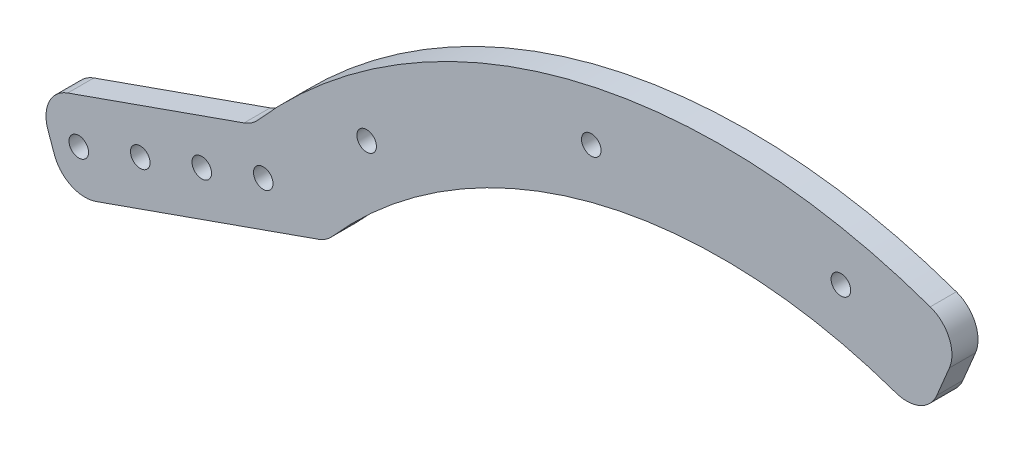
SolidWorks part; units mm, degrees
ref_plane "Front Plane" through (0, 0, 0) normal (0, 0, 1) x (1, 0, 0)
ref_plane "Top Plane" through (0, 0, 0) normal (0, 1, 0) x (1, 0, 0)
ref_plane "Right Plane" through (0, 0, 0) normal (1, 0, 0) x (0, 0, -1)
sketch "Sketch1" plane through (0, 0, 0) normal (0, 0, 1) x (1, 0, 0)
  line L0 (-132.022, 65.7897) -> (-212.1762, 37.5)
  line L1 (51.7662, 161.9592) -> (27.2426, 103.4517) construction
  line L2 (-154.8138, 85.297) -> (-220.8231, 61.9996) construction
  line L3 (-10.6861, 66.0459) -> (-10.9148, 174.3641) construction
  line L4 (-216.4997, 49.7498) -> (-207.0698, 53.078) construction
  line L5 (32.4547, 115.8865) -> (40.5023, 144.7869) construction
  line L6 (-154.8138, 85.297) -> (-220.8231, 61.9996)
  line L7 (-220.8231, 61.9996) -> (-212.1762, 37.5)
  line L8 (-47.4083, 117.4275) -> (-132.022, 65.7897) construction
  line L9 (-89.7151, 91.6086) -> (-121.1048, 143.0437) construction
  line L10 (122.3134, 57.5344) -> (77.0665, 91.5473) construction
  line L11 (-212.1762, 37.5) -> (-212.1762, 7.5) construction
  line L12 (-212.1762, 7.5) -> (-297.1762, 7.5) construction
  line L13 (-297.1762, 7.5) -> (-212.1762, 37.5) construction
  line L14 (-147.9866, 38.946) -> (-93.3561, 58.2274) construction
  line L15 (-93.3561, 58.2274) -> (51.385, 109.3125) construction
  line L16 (184.397, 188.9678) -> (-168.455, 103.7035) construction
  line L17 (51.385, 109.3125) -> (62.982, 136.9803) construction
  line L18 (-0.3193, 248.4877) -> (121.5642, -96.8487) construction
  line L19 (51.385, 109.3125) -> (62.982, 136.9803)
  line L20 (-132.022, 65.7897) -> (51.385, 109.3125) construction
  arc A1 (62.982, 136.9803) -> (-154.8138, 85.297) centre (-10.4659, -38.2493) ccw
  arc A2 (51.385, 109.3125) -> (-132.022, 65.7897) centre (-10.4659, -38.2493) ccw
  dimension "D1" = 30
  dimension "D4" = 160
  dimension "D5" = 190
  dimension "D2" = 85
  dimension "D3" = 25.9808
  dimension "D6" = 85
  dimension "D7" = 20
  dimension "D8" = 20
  dimension "D9" = 10
  dimension "D10" = 260
extrude "Boss-Extrude1" add sketch "Sketch1" along normal blind 8
sketch "Sketch2" plane through (0, 0, 8) normal (0, 0, 1) x (1, 0, 0)
  line L0 (-216.4997, 49.7498) -> (-123.9236, 82.4237) construction
  line L1 (-220.8231, 61.9996) -> (-212.1762, 37.5) construction
  line L3 (42.7389, 166.2908) -> (9.592, 87.2101) construction
  line L4 (51.385, 109.3125) -> (62.982, 136.9803) construction
  line L5 (-154.8138, 85.297) -> (-220.8231, 61.9996) construction
  line L6 (-132.022, 65.7897) -> (51.385, 109.3125) construction
  line L7 (-40.3185, 87.5511) -> (-44.5586, 105.4188) construction
  line L8 (-47.4083, 117.4275) -> (-54.2495, 146.2568) construction
  line L10 (22.6202, 118.2925) -> (115.0547, 98.7558) construction
  line L11 (22.6202, 118.2925) -> (28.8239, 147.644) construction
  circle A0 centre (-208.0128, 52.7452) radius 3
  circle A1 centre (-189.153, 59.4016) radius 3
  arc A2 (62.982, 136.9803) -> (-154.8138, 85.297) centre (-10.4659, -38.2493) ccw construction
  circle A3 centre (-170.2932, 66.058) radius 3
  circle A4 centre (-151.4334, 72.7144) radius 3
  circle A6 centre (25.722, 132.9682) radius 3
  arc A8 (51.385, 109.3125) -> (-132.022, 65.7897) centre (-10.4659, -38.2493) ccw construction
  circle A9 centre (-50.8289, 131.8422) radius 3
  arc A11 (51.385, 109.3125) -> (-132.022, 65.7897) centre (-10.4659, -38.2493) ccw construction
  circle A12 centre (-119.7239, 98.4537) radius 3
  dimension "D1" = 6
  dimension "D3" = 20
  dimension "D2" = 9
  dimension "D4" = 20
  dimension "D5" = 30
  dimension "D7" = 20
extrude "Cut-Extrude1" cut sketch "Sketch2" against normal offset from surface (7.8 mm away) 0.2 up to face at (-103.4962, 93.7056, 0)
fillet "Fillet1" radius 10 6 edges at (-212.1762, 37.5, 4) (-220.8231, 61.9996, 4) (-154.8138, 85.297, 4) (-132.022, 65.7897, 4) (51.385, 109.3125, 4) (62.982, 136.9803, 4)
